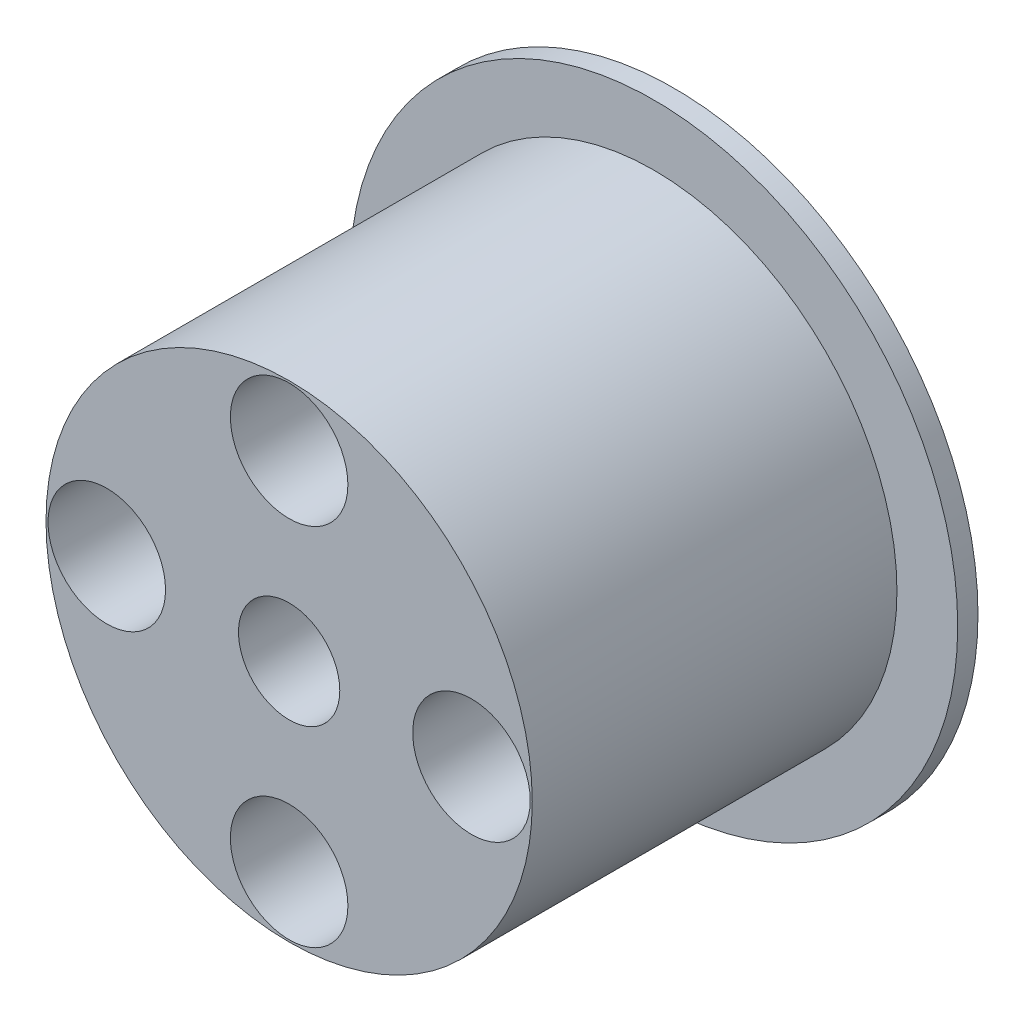
SolidWorks part; units mm, degrees
ref_plane "Ebene vorne" through (0, 0, 0) normal (0, 0, 1) x (1, 0, 0)
ref_plane "Ebene oben" through (0, 0, 0) normal (0, 1, 0) x (1, 0, 0)
ref_plane "Ebene rechts" through (0, 0, 0) normal (1, 0, 0) x (0, 0, -1)
sketch "Skizze1" plane through (0, 0, 0) normal (0, 0, 1) x (1, 0, 0)
  circle A0 centre (0, 0) radius 12
  circle A1 centre (0, 0) radius 9
  circle A2 centre (9, 0) radius 1.5
  circle A3 centre (0, -9) radius 1.5
  circle A4 centre (-9, 0) radius 1.5
  circle A5 centre (0, 9) radius 1.5
  point P15 (0, 0)
  dimension "D1" = 24
  dimension "D2" = 18
  dimension "D3" = 4
extrude "Aufsatz-Linear austragen1" add sketch "Skizze1" along normal blind 18 contours A1 | A0 A1 | A4 | A2 | A5 | A3
sketch "Skizze4" plane through (0, 0, 0) normal (0, 0, -1) x (-1, 0, 0)
  circle A0 centre (0, 0) radius 15
  circle A1 centre (0, 9) radius 1.5
  circle A2 centre (9, 0) radius 1.5
  circle A3 centre (0, -9) radius 1.5
  circle A4 centre (-9, 0) radius 1.5
extrude "Aufsatz-Linear austragen2" add sketch "Skizze4" along normal blind 1
sketch "Skizze2" plane through (0, 0, 18) normal (0, 0, 1) x (1, 0, 0)
  circle A0 centre (0, 9) radius 2.9
  circle A1 centre (9, 0) radius 2.9
  circle A2 centre (0, -9) radius 2.9
  circle A3 centre (-9, 0) radius 2.9
  point P12 (0, 0)
  dimension "D1" = 4
extrude "Schnitt-Linear austragen4" cut sketch "Skizze2" against normal offset from surface (14 mm away) 5 up to face at (-1.5, -9, -1)
sketch "Skizze6" plane through (0, 0, 18) normal (0, 0, 1) x (1, 0, 0)
  line L0 (-1.5, 2) -> (1.5, 2)
  circle A0 centre (0, 0) radius 2.5
  dimension "D1" = 5
  dimension "D2" = 3
extrude "Schnitt-Linear austragen5" cut sketch "Skizze6" against normal blind 23 contours L0 A0
sketch "Skizze9" plane through (0, 0, 18) normal (0, 0, 1) x (1, 0, 0)
  circle A0 centre (0, 0) radius 2.5
extrude "Schnitt-Linear austragen7" cut sketch "Skizze9" against normal blind 5
